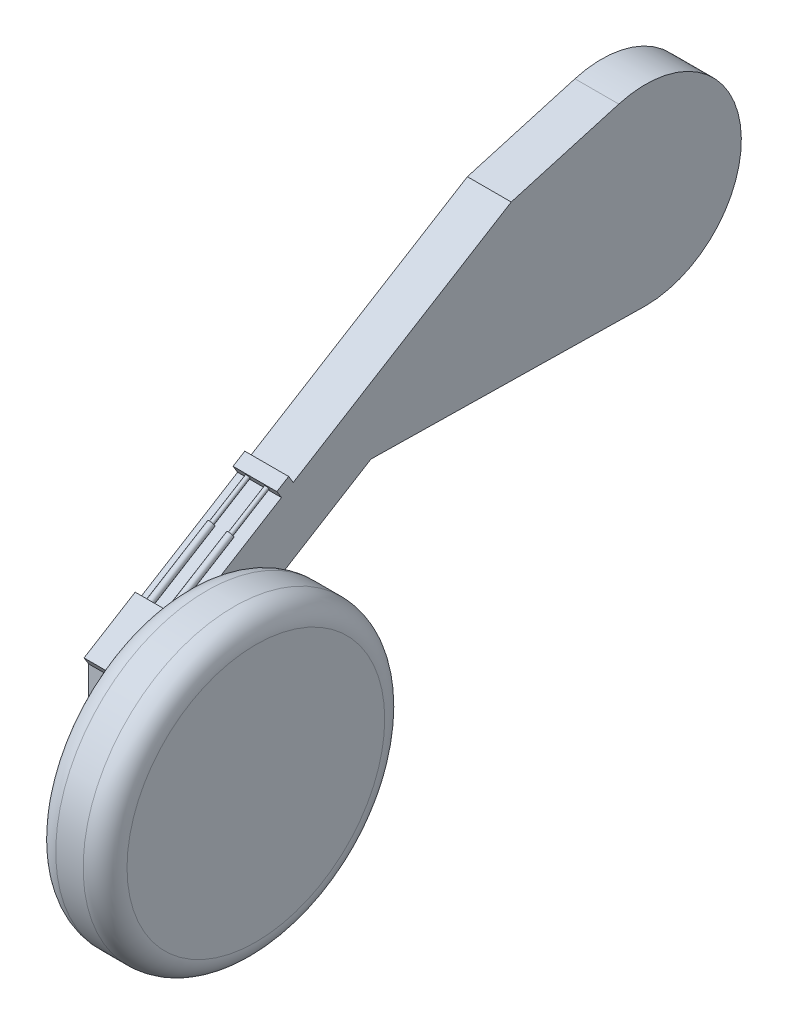
SolidWorks part; units mm, degrees
ref_plane "Front Plane" through (0, 0, 0) normal (0, 0, 1) x (1, 0, 0)
ref_plane "Top Plane" through (0, 0, 0) normal (0, 1, 0) x (1, 0, 0)
ref_plane "Right Plane" through (0, 0, 0) normal (1, 0, 0) x (0, 0, -1)
sketch "Sketch1" plane through (0, 0, 0) normal (1, 0, 0) x (0, 0, -1)
  line L0 (-48.5046, 168.1437) -> (-244.6834, 111.5518)
  line L1 (-244.6834, 111.5518) -> (-935.4804, -312.6439)
  line L2 (-935.4804, -312.6439) -> (-935.4804, -439.6183)
  line L3 (-935.4804, -439.6183) -> (-846.647, -439.6183)
  line L4 (-846.647, -439.6183) -> (-846.647, -379.0792)
  line L5 (-846.647, -379.0792) -> (-500.6229, -166.5972)
  line L6 (-500.6229, -166.5972) -> (0, -175)
  arc A0 (0, -175) -> (-48.5046, 168.1437) centre (0, 0) ccw
  dimension "D1" = 350
extrude "Boss-Extrude1" add sketch "Sketch1" along normal blind 80
sketch "Sketch3" plane through (0, 0, 0) normal (-1, 0, 0) x (0, 0, 1)
  circle A0 centre (0, 0) radius 50
  dimension "D1" = 100
extrude "Cut-Extrude1" cut sketch "Sketch3" against normal blind 60
sketch "Sketch4" plane through (0, 190.1154, 116.7436) normal (0, 0.8522, 0.5233) x (1, 0, 0)
  line L0 (0, -150.136) -> (0, -960.7793) construction
  line L1 (80, -616.7483) -> (0, -616.7483)
  line L2 (80, -616.7483) -> (80, -641.9376)
  line L3 (80, -641.9376) -> (0, -641.9376)
  line L4 (0, -616.7483) -> (0, -641.9376)
  line L5 (80, -616.7483) -> (0, -641.9376) construction
  line L6 (80, -641.9376) -> (0, -616.7483) construction
  point P0 (40, -629.343)
extrude "Boss-Extrude2" add sketch "Sketch4" along normal blind 16
sketch "Sketch5" plane through (0, 190.1154, 116.7436) normal (0, 0.8522, 0.5233) x (1, 0, 0)
  line L1 (80, -851.3398) -> (0, -851.3398)
  line L2 (80, -851.3398) -> (80, -960.7793)
  line L3 (80, -960.7793) -> (0, -960.7793)
  line L4 (0, -851.3398) -> (0, -960.7793)
  line L5 (80, -851.3398) -> (0, -960.7793) construction
  line L6 (80, -960.7793) -> (0, -851.3398) construction
  point P0 (40, -906.0596)
extrude "Boss-Extrude3" add sketch "Sketch5" along normal blind 16
sketch "Sketch6" plane through (0, -335.9149, 547.033) normal (0, -0.5233, 0.8522) x (1, 0, 0)
  line L0 (40, 239.0985) -> (40, 439.461) construction
  line L1 (0, 239.0985) -> (80, 239.0985) construction
  circle A0 centre (22.6697, 230.9448) radius 3.8346
  circle A1 centre (57.3303, 230.9448) radius 3.8346
extrude "Boss-Extrude4" add sketch "Sketch6" along normal blind 78
sketch "Sketch7" plane through (0, -376.731, 613.5014) normal (0, -0.5233, 0.8522) x (1, 0, 0)
  circle A0 centre (22.6697, 230.9448) radius 6
  circle A1 centre (57.3303, 230.9448) radius 6
  dimension "D1" = 12
  dimension "D2" = 12
extrude "Boss-Extrude5" add sketch "Sketch7" along normal blind 135
sketch "Sketch9" plane through (80, 0, 0) normal (1, 0, 0) x (0, 0, -1)
  line L0 (-935.4804, -312.6439) -> (-935.4804, -439.6183) construction
  line L1 (-935.4804, -439.6183) -> (-846.647, -439.6183) construction
  circle A0 centre (-890.4804, -409.6183) radius 20
  dimension "D1" = 40
  dimension "D2" = 45
  dimension "D3" = 30
extrude "Boss-Extrude6" add sketch "Sketch9" along normal blind 50
sketch "Sketch10" plane through (130, 0, 0) normal (1, 0, 0) x (0, 0, -1)
  circle A0 centre (-890.4804, -409.6183) radius 275
  dimension "D1" = 550
extrude "Boss-Extrude7" add sketch "Sketch10" along normal blind 130
fillet "Fillet1" radius 40 2 edges at (260, -409.6183, 615.4804) (130, -409.6183, 615.4804)
